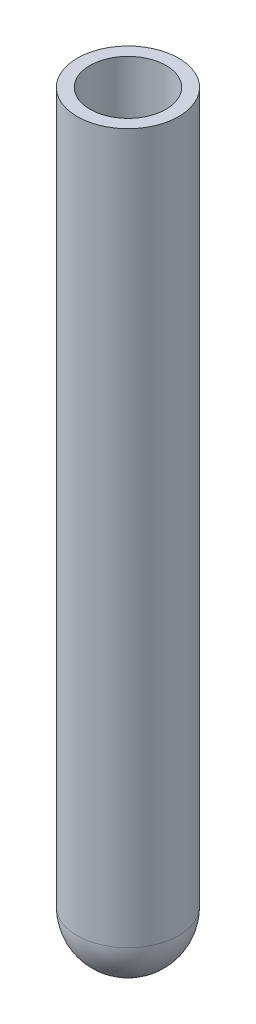
SolidWorks part; units mm, degrees
ref_plane "Front Plane" through (0, 0, 0) normal (0, 0, 1) x (1, 0, 0)
ref_plane "Top Plane" through (0, 0, 0) normal (0, 1, 0) x (1, 0, 0)
ref_plane "Right Plane" through (0, 0, 0) normal (1, 0, 0) x (0, 0, -1)
sketch "Sketch2" plane through (0, 0, 0) normal (0, 0, 1) x (1, 0, 0)
  line L0 (0, 0) -> (5, 0) construction
  line L1 (0, 0) -> (-5, 0) construction
  line L2 (-5, 0) -> (0, 0)
  line L3 (0, 0) -> (0, 7.7878) construction
  line L4 (0, 0) -> (0, -5)
  arc A0 (-5, 0) -> (0, -5) centre (0, 0) ccw
  dimension "D1" = 5
revolve "Revolve1" add sketch "Sketch2" angle 360 about L3
sketch "Sketch3" plane through (0, 0, 0) normal (0, 1, 0) x (1, 0, 0)
  circle A0 centre (0, 0) radius 5
  circle A1 centre (0, 0) radius 3.75
  point P4 (0, 0)
  dimension "D1" = 7.5
extrude "Boss-Extrude1" add sketch "Sketch3" along normal blind 70
